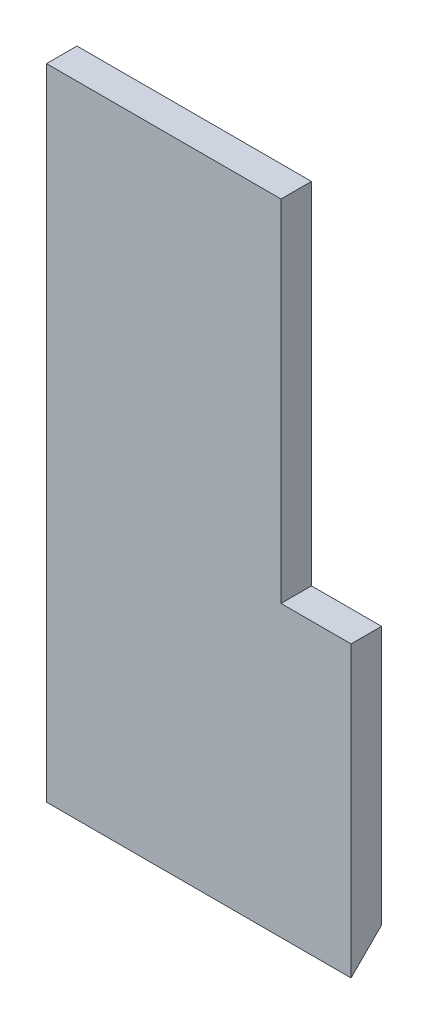
SolidWorks part; units mm, degrees
ref_plane "Plan de face" through (0, 0, 0) normal (0, 0, 1) x (1, 0, 0)
ref_plane "Plan de dessus" through (0, 0, 0) normal (0, 1, 0) x (1, 0, 0)
ref_plane "Plan de droite" through (0, 0, 0) normal (1, 0, 0) x (0, 0, -1)
sketch "Esquisse1" plane through (0, 0, 0) normal (0, 0, 1) x (1, 0, 0)
  line L1 (-50, -105) -> (50, -105)
  line L2 (-50, -105) -> (-50, 105)
  line L3 (-50, 105) -> (27, 105)
  line L4 (50, -105) -> (50, -10)
  line L7 (27, 105) -> (27, -10) construction
  line L8 (27, 105) -> (27, -10)
  line L9 (27, -10) -> (50, -10)
  point P0 (0, 0)
  dimension "D1" = 210
  dimension "D2" = 100
  dimension "D4" = 115
extrude "Boss.-Extru.1" add sketch "Esquisse1" along normal blind 10 contours L3 L8 L9 L4 L1 L2
ref_plane "Plan3" through (50, 0, 0) normal (1, 0, 0) x (0, 0, -1)
sketch "Esquisse7" plane through (50, 0, 0) normal (1, 0, 0) x (0, 0, -1)
  line L0 (-10, -105) -> (0, -105)
  line L1 (-10, -105) -> (0, -95)
  line L2 (0, -105) -> (0, -10) construction
  line L3 (0, -95) -> (0, -105)
  dimension "D1" = 45
extrude "Enlèv. mat.-Extru.1" cut sketch "Esquisse7" against normal blind 100
